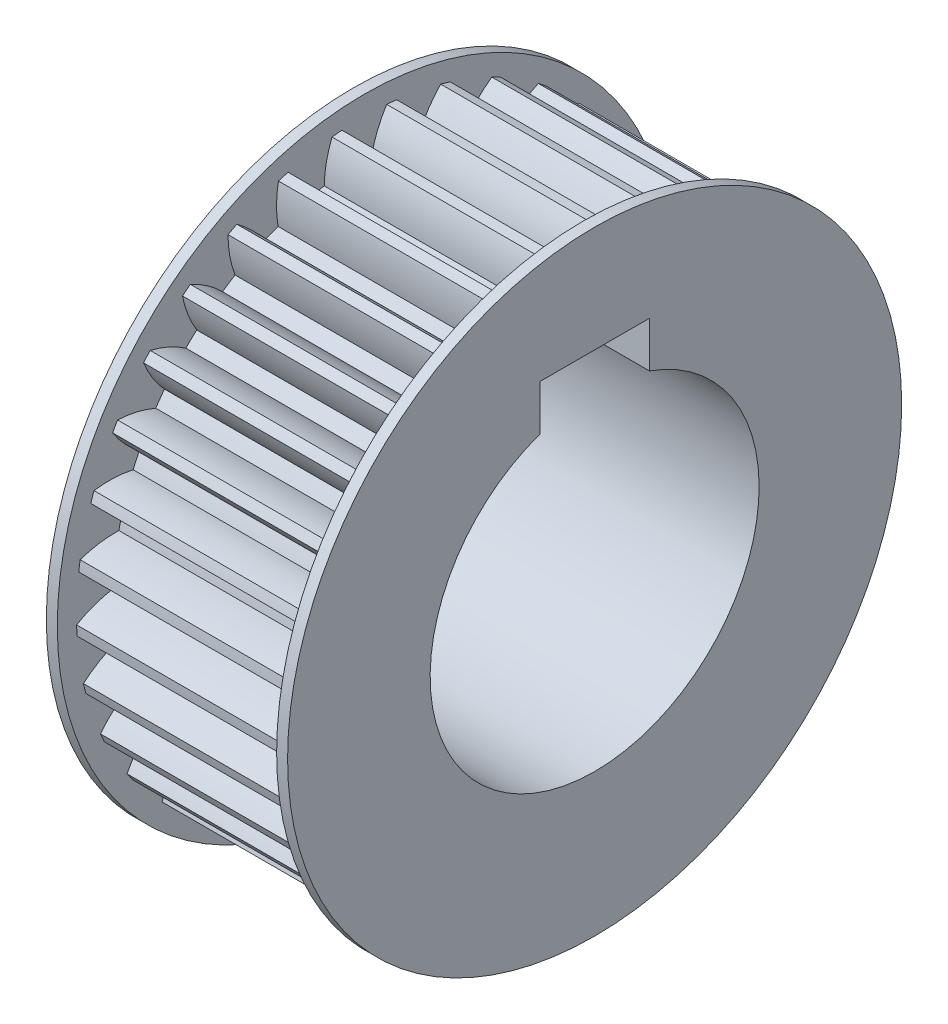
SolidWorks part; units mm, degrees
ref_plane "Plane1" through (0, 0, 0) normal (0, 0, 1) x (1, 0, 0)
ref_plane "Plane2" through (0, 0, 0) normal (0, 1, 0) x (1, 0, 0)
ref_plane "Plane3" through (0, 0, 0) normal (1, 0, 0) x (0, 0, -1)
sketch "HoldingSke" plane through (0, 0, 0) normal (0, 1, 0) x (1, 0, 0)
  line L0 (0, 0) -> (0.5591, -0.3631)
  line L1 (-15, 0) -> (100, 0) construction
  line L2 (0, 0) -> (-2.1039, 2.3779)
  line L3 (0, 0) -> (-11.863, 4.5341)
  line L4 (0, 0) -> (7.2428, 4.7035)
  line L5 (0, 0) -> (-46.8476, -17.4728)
  line L6 (0, 0) -> (-16.5793, -11.1861)
  line L7 (-2.1039, 2.3779) -> (8.6586, 51.2059)
  line L8 (-76.2, 54.61) -> (-72.9, 54.61)
  line L9 (-71.009, 38.7566) -> (-53.1078, 45.2721)
  line L10 (-76.2, 71.12) -> (104.1128, 71.12)
  line L11 (0, 0) -> (-20, 0)
  line L12 (-76.2, 101.6) -> (-76.147, 101.6)
  line L13 (24.9733, 27.94) -> (52.9518, 28.4284)
  line L14 (24.9733, 27.94) -> (24.9743, 27.94)
  line L15 (24.9733, 27.94) -> (100.4006, 29.5858)
  line L16 (-63.627, -1.5) -> (-12.827, -1.5)
  circle A0 centre (0, 0) radius 15
  circle A1 centre (0, 0) radius 22.874
  circle A2 centre (0, 0) radius 37.5
  circle A3 centre (0, 0) radius 15
  dimension "MHD" = 45.748
  dimension "Hub_dia" = 75
  dimension "Bore" = 30
  dimension "MBD" = 30
  dimension "Num_teeth" = 33
  dimension "Pitch" = 0.6667
  dimension "Overall_len" = 50
  dimension "Show_teeth" = 33
  dimension "Thickness" = 20
  dimension "OAL" = 50.0001
  dimension "T_dim" = 3.3
  dimension "Ap" = 20
  dimension "H" = 19.05
  dimension "Pitch_radius" = 180.3128
  dimension "Width" = 20
  dimension "Backlash" = 0.053
  dimension "Addendum_fac" = 1
  dimension "Dedendum_fac" = 1.25
  dimension "Clearance_fac" = 0.25
  dimension "Dedendum_add" = 0.001
  dimension "Module" = 1.5
sketch "BasProSke" plane through (0, 0, 0) normal (0, 1, 0) x (1, 0, 0)
  line L0 (-10, 0) -> (60, 0) construction
  line L1 (0, 0) -> (0, 26.25)
  line L2 (0, 0) -> (20, 0)
  line L3 (20, 0) -> (20, 26.25)
  line L4 (20, 26.25) -> (0, 26.25)
  dimension "Thickness" = 20
  dimension "Diameter" = 52.5
revolve "Base-Revolve" add sketch "BasProSke" angle 360 about L0
sketch "TooCutSke" plane through (0, 0, 0) normal (1, 0, 0) x (0, 0, -1)
  line L1 (0, 0) -> (0, 107) construction
  line L2 (0, 0) -> (-1.2704, 24.7174) construction
  line L3 (0, 0) -> (-4.7008, 49.2285) construction
  line L4 (-1.2704, 24.7174) -> (-2.3504, 24.6142) construction
  arc A0 (0.6837, 22.8638) -> (-0.6837, 22.8638) centre (0, 0) ccw
  arc A1 (2.0575, 26.1947) -> (-2.0575, 26.1947) centre (0, 0) ccw
  circle A2 centre (0, 0) radius 24.75 construction
  circle A3 centre (0, 0) radius 23.2574 construction
  arc A4 (-0.6837, 22.8638) -> (-2.0575, 26.1947) centre (-10.3699, 20.8176) ccw
  arc A5 (2.0575, 26.1947) -> (0.6837, 22.8638) centre (10.3699, 20.8176) ccw
  dimension "Root_dia" = 45.748
  dimension "Overcut_dia" = 52.5508
  dimension "Pitch_dia" = 49.5
  dimension "Base_dia" = 46.5148
  dimension "Flank_rad" = 9.9
  dimension "Half_ang" = 5.455
  dimension "Half_CT" = 1.0849
extrude "ToothCut" cut sketch "TooCutSke" along normal through all
fillet "Breaks" [suppressed] radius 0.03
fillet "RootFillets" [suppressed] radius 0.376
pattern_circular "TeethCuts" count 33 every 10.909 about axis through (-10, 0, 0) along (1, 0, 0) of "ToothCut", "RootFillets", "Breaks"
sketch "HubNeaOneSke" plane through (0, 0, 0) normal (-1, 0, 0) x (0, 0, 1)
  circle A0 centre (0, 0) radius 22.874
  dimension "Diameter" = 45.748
extrude "HubNearOne" [suppressed] add sketch "HubNeaOneSke" along normal blind 30.0001
sketch "HubNeaBotSke" plane through (0, 0, 0) normal (-1, 0, 0) x (0, 0, 1)
  circle A0 centre (0, 0) radius 22.874
  dimension "Diameter" = 45.748
extrude "HubNearBoth" [suppressed] add sketch "HubNeaBotSke" along normal blind 15
ref_plane "FarPln" through (20, 0, 0) normal (1, 0, 0) x (0, 0, -1)
sketch "HubFarSke" plane through (20, 0, 0) normal (1, 0, 0) x (0, 0, -1)
  circle A0 centre (0, 0) radius 22.874
  dimension "Diameter" = 45.748
extrude "HubFar" [suppressed] add sketch "HubFarSke" along normal blind 15
sketch "BorSke" plane through (0, 0, 0) normal (1, 0, 0) x (0, 0, -1)
  circle A0 centre (0, 0) radius 15
  dimension "Diameter" = 30
extrude "Bore" cut sketch "BorSke" along normal mid plane 100.0001
sketch "KeySke" plane through (0, 0, 0) normal (1, 0, 0) x (0, 0, -1)
  line L0 (-5, 0) -> (-5, 18.3)
  line L1 (-5, 18.3) -> (5, 18.3)
  line L2 (5, 18.3) -> (5, 0)
  line L3 (0, 0) -> (0, 34) construction
  line L4 (-5, 0) -> (5, 0)
  dimension "Offset" = 18.3
  dimension "Width" = 10
extrude "Keyway" cut sketch "KeySke" along normal mid plane 100.0001
pattern_circular "Keyway2" [suppressed] count 2 every 90 about axis through (-10, 0, 0) along (1, 0, 0)
sketch "Эскиз1" plane through (20, 0, 0) normal (1, 0, 0) x (0, 0, -1)
  line L0 (5, 18.3) -> (-5, 18.3) construction
  line L2 (5, 14.1421) -> (5, 18.3) construction
  line L3 (-5, 18.3) -> (-5, 14.1421) construction
  line L4 (5, 18.3) -> (-5, 18.3)
  line L5 (5, 14.1421) -> (5, 18.3)
  line L6 (-5, 18.3) -> (-5, 14.1421)
  circle A2 centre (0, 0) radius 28
  arc A4 (-5, 14.1421) -> (5, 14.1421) centre (0, 0) ccw construction
  arc A5 (-5, 14.1421) -> (5, 14.1421) centre (0, 0) ccw
  dimension "D1" = 56
extrude "Бобышка-Вытянуть2" add sketch "Эскиз1" along normal blind 1 contours A2
sketch "Эскиз2" plane through (0, 0, 0) normal (-1, 0, 0) x (0, 0, 1)
  line L0 (-5, 18.3) -> (-5, 14.1421) construction
  line L1 (5, 18.3) -> (-5, 18.3) construction
  line L2 (5, 14.1421) -> (5, 18.3) construction
  line L3 (-5, 18.3) -> (-5, 14.1421)
  line L4 (5, 18.3) -> (-5, 18.3)
  line L5 (5, 14.1421) -> (5, 18.3)
  arc A0 (-5, 14.1421) -> (5, 14.1421) centre (0, 0) ccw construction
  circle A1 centre (0, 0) radius 28 construction
  arc A2 (-5, 14.1421) -> (5, 14.1421) centre (0, 0) ccw
  circle A3 centre (0, 0) radius 28
extrude "Бобышка-Вытянуть3" add sketch "Эскиз2" along normal blind 1
equation "' \"Module@HoldingSke\" = 6.35"
equation "' \"Num_teeth@HoldingSke\" = 12"
equation "' \"Ap@HoldingSke\" =  20"
equation "' \"Ap@HoldingSke\" = 20"
equation "' \"Width@HoldingSke\" = 0.5 * 25.4"
equation "' \"Hub_dia@HoldingSke\"= 1 * 25.4"
equation "' \"Hub_dia@HoldingSke\" = 1 * 25.4"
equation "' \"Overall_len@HoldingSke\" = 1.0 * 25.4"
equation "' \"Bore@HoldingSke\" = 0.75 * 25.4"
equation "' \"T_dim@HoldingSke\" = 0.1 * 25.4"
equation "' \"Width@KeySke\" = 0.25 * 25.4"
equation "' \"Show_teeth@HoldingSke\" = 13"
equation "' \"Backlash@HoldingSke\" = 0.009 * 25.4"
equation "' \"Addendum_fac@HoldingSke\" = 1.0"
equation "' \"Dedendum_fac@HoldingSke\" = 1.25"
equation "' \"Dedendum_add@HoldingSke\" = 0.00005 * 25.4"
equation "' \"Clearance_fac@HoldingSke\" = 0.25"
equation "\"Pitch@HoldingSke\" = 1 / \"Module@HoldingSke\""
equation "\"Overcut_dia@TooCutSke\" = (\"Num_teeth@HoldingSke\" + 2 * \"Addendum_fac@HoldingSke\") / \"Pitch@HoldingSke\" + 0.002 * 25.4"
equation "\"Pitch_dia@TooCutSke\" = \"Num_teeth@HoldingSke\" / \"Pitch@HoldingSke\""
equation "\"Base_dia@TooCutSke\" = \"Num_teeth@HoldingSke\" / \"Pitch@HoldingSke\" * cos((\"Ap@HoldingSke\"  * 3.14159265 / 180))"
equation "\"Root_dia@TooCutSke\" = (\"Num_teeth@HoldingSke\" + 2) / \"Pitch@HoldingSke\" - 2 * (\"Addendum_fac@HoldingSke\" + \"Dedendum_fac@HoldingSke\") / \"Pitch@HoldingSke\" - \"Dedendum_add@HoldingSke\" * 2"
equation "\"Half_ang@TooCutSke\" = 180 / \"Num_teeth@HoldingSke\""
equation "\"Half_CT@TooCutSke\" = \"Num_teeth@HoldingSke\" / \"Pitch@HoldingSke\" * sin((3.14159265 / 2 / \"Num_teeth@HoldingSke\")) / 2 - 7 * \"Backlash@HoldingSke\" / 4"
equation "\"Flank_rad@TooCutSke\" = \"Num_teeth@HoldingSke\" / \"Pitch@HoldingSke\" / 5"
equation "\"Radius@RootFillets\" = \"Clearance_fac@HoldingSke\" / \"Pitch@HoldingSke\" + \"Dedendum_add@HoldingSke\""
equation "\"Break_rad@Breaks\" = 0.02 / \"Pitch@HoldingSke\""
equation "\"Thickness@HoldingSke\" = \"Width@HoldingSke\""
equation "\"OAL@HoldingSke\" = \"Thickness@HoldingSke\""
equation "\"MHD@HoldingSke\" = (\"Num_teeth@HoldingSke\" + 2) / \"Pitch@HoldingSke\" - 2 * (\"Addendum_fac@HoldingSke\" + \"Dedendum_fac@HoldingSke\")  / \"Pitch@HoldingSke\" - \"Dedendum_add@HoldingSke\" * 2"
equation "\"MBD@HoldingSke\" = (\"Num_teeth@HoldingSke\" + 2) / \"Pitch@HoldingSke\" - 2 * (\"Addendum_fac@HoldingSke\" + \"Dedendum_fac@HoldingSke\")  / \"Pitch@HoldingSke\" - \"Dedendum_add@HoldingSke\" * 2 - 0.002 * 25.4"
equation "\"MHD@HoldingSke\" = ((sgn( \"MHD@HoldingSke\" - \"Hub_dia@HoldingSke\" )-1)*( \"MHD@HoldingSke\" - \"Hub_dia@HoldingSke\" ))/-2+ \"Hub_dia@HoldingSke\""
equation "\"MBD@HoldingSke\" = ((sgn( \"MBD@HoldingSke\" - \"Bore@HoldingSke\" )-1)*( \"MBD@HoldingSke\" - \"Bore@HoldingSke\" ))/-2+ \"Bore@HoldingSke\""
equation "\"OAL@HoldingSke\" = ((sgn( \"OAL@HoldingSke\" - \"Overall_len@HoldingSke\" )+1)*( \"OAL@HoldingSke\" - \"Overall_len@HoldingSke\" ))/2 + \"Overall_len@HoldingSke\" + 0.000002 * 25.4"
equation "\"Num_teeth@TeethCuts\" = int( \"Show_teeth@HoldingSke\" ) + 1"
equation "\"Num_teeth@TeethCuts\" = ((sgn( \"Num_teeth@TeethCuts\" - \"Num_teeth@HoldingSke\" )-1)*( \"Num_teeth@TeethCuts\" - \"Num_teeth@HoldingSke\" ))/-2+ \"Num_teeth@HoldingSke\""
equation "\"Num_teeth@TeethCuts\" = ((sgn( \"Num_teeth@TeethCuts\" - 2.0)+1)*( \"Num_teeth@TeethCuts\" - 2.0))/2 +2.0"
equation "\"Angle@TeethCuts\" = 360.0 / \"Num_teeth@HoldingSke\""
equation "\"Diameter@BasProSke\" = (\"Num_teeth@HoldingSke\" + 2 * \"Addendum_fac@HoldingSke\") / \"Pitch@HoldingSke\""
equation "\"Thickness@BasProSke\"  = \"Thickness@HoldingSke\""
equation "' \"Fillet_rad@BasProSke\" =  \"Thickness@HoldingSke\" * 0.05"
equation "' \"Fillet_rad@BasProSke\" = \"Thickness@HoldingSke\" * 0.05"
equation "\"MHD@HoldingSke\" = ((sgn( \"MHD@HoldingSke\" - \"Root_dia@TooCutSke\" )-1)*( \"MHD@HoldingSke\" - \"Root_dia@TooCutSke\" ))/-2+ \"Root_dia@TooCutSke\""
equation "\"Diameter@HubNeaOneSke\" = \"MHD@HoldingSke\""
equation "\"Length@HubNearOne\" = \"OAL@HoldingSke\" - \"Thickness@BasProSke\""
equation "\"Diameter@HubNeaBotSke\" = \"MHD@HoldingSke\""
equation "\"Length@HubNearBoth\" = ( \"OAL@HoldingSke\" - \"Thickness@BasProSke\" ) / 2.0"
equation "\"Thickness@FarPln\" = \"Thickness@BasProSke\""
equation "\"Diameter@HubFarSke\" = \"MHD@HoldingSke\""
equation "\"Length@HubFar\" = ( \"OAL@HoldingSke\" - \"Thickness@BasProSke\" ) / 2.0"
equation "\"Diameter@BorSke\" = \"MBD@HoldingSke\""
equation "\"D1@Bore\" = \"OAL@HoldingSke\" * 2.0"
equation "\"D1@Keyway\" = \"OAL@HoldingSke\" * 2.0"
equation "\"Offset@KeySke\" = \"T_dim@HoldingSke\" + \"MBD@HoldingSke\" / 2.0"
